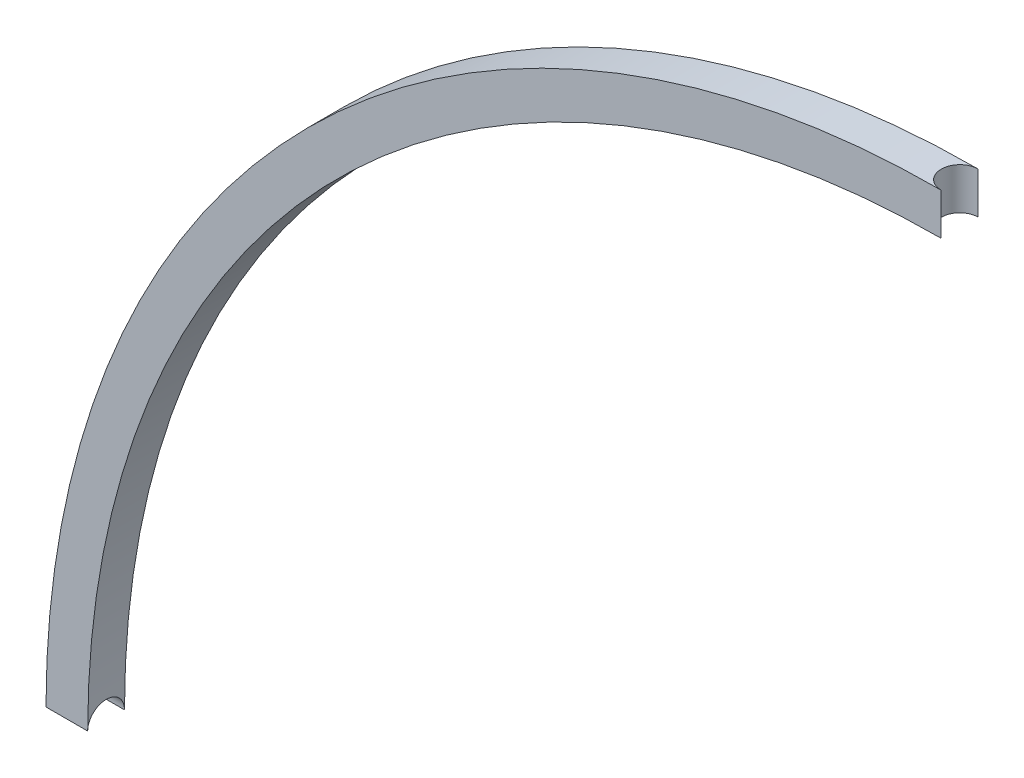
SolidWorks part; units mm, degrees
ref_plane "Front Plane" through (0, 0, 0) normal (0, 0, 1) x (1, 0, 0)
ref_plane "Top Plane" through (0, 0, 0) normal (0, 1, 0) x (1, 0, 0)
ref_plane "Right Plane" through (0, 0, 0) normal (1, 0, 0) x (0, 0, -1)
sketch "Sketch2" plane through (0, 0, 0) normal (0, 0, 1) x (1, 0, 0)
  line L0 (0, 139.2) -> (0, 146)
  line L1 (-139.2, 0) -> (-146, 0)
  arc A0 (0, 139.2) -> (-139.2, 0) centre (0, 0) ccw
  arc A1 (0, 146) -> (-146, 0) centre (0, 0) ccw
  circle A3 centre (0, 0) radius 146 construction
  circle A4 centre (0, 0) radius 139.2 construction
  point P4 (132.6873, 40.5666)
  point P5 (145.55, 0)
  dimension "D1" = 278.4
  dimension "D2" = 6.8
extrude "Boss-Extrude1" add sketch "Sketch2" along normal blind 6
sketch "Sketch3" plane through (0, 0, 0) normal (1, 0, 0) x (0, 0, -1)
  line L0 (-6, 0) -> (0, 0) construction
  circle A0 centre (-3, 0) radius 3
extrude "Cut-Extrude1" cut sketch "Sketch3" against normal blind 172
sketch "Sketch4" plane through (0, 0, 0) normal (0, 1, 0) x (1, 0, 0)
  line L0 (0, -6) -> (0, 0) construction
  circle A0 centre (0, -3) radius 3
extrude "Cut-Extrude2" cut sketch "Sketch4" along normal blind 175
